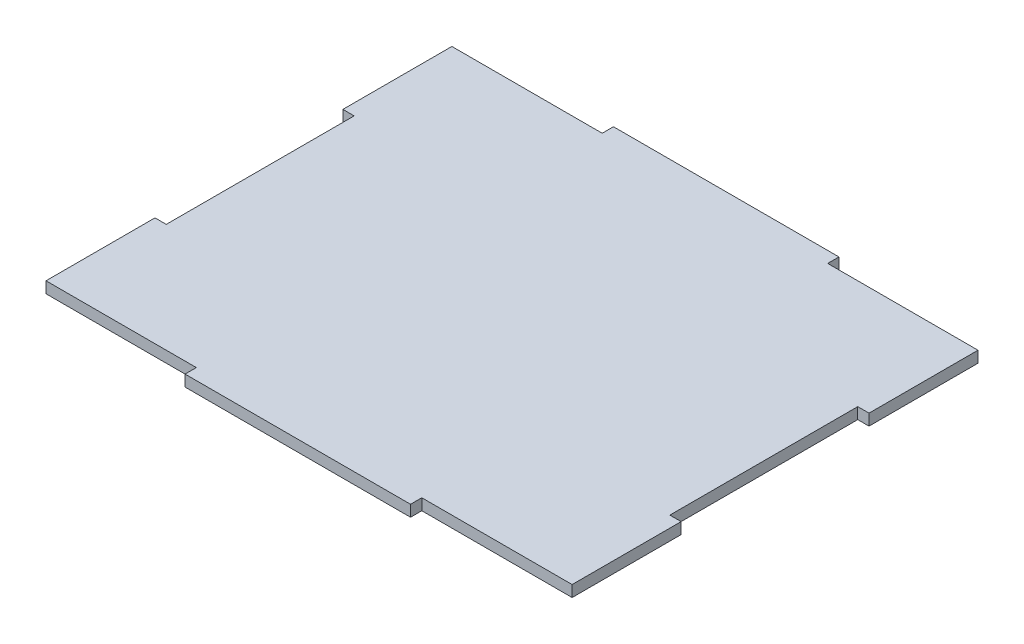
SolidWorks part; units mm, degrees
ref_plane "Спереди" through (0, 0, 0) normal (0, 0, 1) x (1, 0, 0)
ref_plane "Сверху" through (0, 0, 0) normal (0, 1, 0) x (1, 0, 0)
ref_plane "Справа" through (0, 0, 0) normal (1, 0, 0) x (0, 0, -1)
other "Configuration Table"
sketch "Эскиз1" plane through (0, 0, 0) normal (0, 1, 0) x (1, 0, 0)
  line L0 (0, 3) -> (40, 3)
  line L1 (0, 0) -> (140, 0) construction
  line L2 (0, 0) -> (0, 114) construction
  line L3 (0, 114) -> (140, 114) construction
  line L4 (140, 0) -> (140, 114) construction
  line L5 (40, 3) -> (40, 0)
  line L6 (0, 57) -> (140, 57) construction
  line L7 (70, 114) -> (70, 0) construction
  line L8 (0, 32) -> (3, 32)
  line L9 (3, 32) -> (3, 82)
  line L10 (0, 32) -> (0, 3)
  line L11 (40, 0) -> (100, 0)
  line L12 (140, 32) -> (140, 3)
  line L13 (137, 32) -> (137, 82)
  line L14 (140, 32) -> (137, 32)
  line L15 (100, 3) -> (100, 0)
  line L16 (140, 3) -> (100, 3)
  line L17 (0, 114) -> (140, 114) construction
  line L18 (140, 111) -> (100, 111)
  line L19 (100, 111) -> (100, 114)
  line L20 (140, 82) -> (137, 82)
  line L21 (140, 82) -> (140, 111)
  line L22 (40, 114) -> (100, 114)
  line L23 (0, 82) -> (0, 111)
  line L24 (0, 82) -> (3, 82)
  line L25 (40, 111) -> (40, 114)
  line L26 (0, 111) -> (40, 111)
  point P26 (137, 57)
  point P30 (3, 57)
  point P31 (1.5, 32)
  point P32 (140, 96.5)
  point P33 (100, 112.5)
  dimension "D1" = 32
  dimension "D2" = 114
  dimension "D3" = 50
  dimension "D4" = 40
  dimension "D5" = 140
  dimension "D6" = 60
  dimension "D7" = 3
  dimension "D8" = 3
extrude "Бобышка-Вытянуть1" add sketch "Эскиз1" along normal blind 3 contours L22 L19 L18 L21 L20 L13 L14 L12 L16 L15 L11 L5 L0 L10 L8 L9 L24 L23 L26 L25
